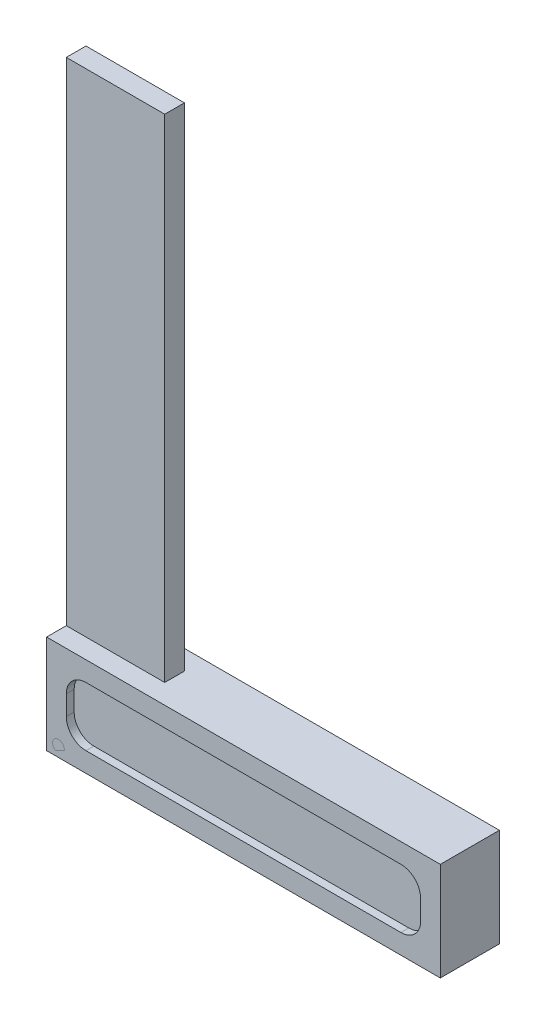
SolidWorks part; units mm, degrees
ref_plane "Plan de face" through (0, 0, 0) normal (0, 0, 1) x (1, 0, 0)
ref_plane "Plan de dessus" through (0, 0, 0) normal (0, 1, 0) x (1, 0, 0)
ref_plane "Plan de droite" through (0, 0, 0) normal (1, 0, 0) x (0, 0, -1)
sketch "Esquisse1" plane through (0, 0, 0) normal (0, 0, 1) x (1, 0, 0)
  line L1 (0, 0) -> (100, 0)
  line L2 (0, 0) -> (0, 25)
  line L3 (0, 25) -> (100, 25)
  line L4 (100, 0) -> (100, 25)
  dimension "D1" = 25
  dimension "D2" = 100
extrude "Boss.-Extru.1" add sketch "Esquisse1" along normal blind 15
sketch "Esquisse2" plane through (0, 0, 0) normal (-1, 0, 0) x (0, 0, 1)
  line L0 (15, 0) -> (0, 0) construction
  line L1 (5, 0) -> (10, 0)
  line L2 (5, 0) -> (5, 25)
  line L4 (10, 0) -> (10, 25)
  line L5 (15, 25) -> (0, 25) construction
  line L6 (7.5, 0) -> (7.5, 25) construction
  line L7 (5, 25) -> (5, 150)
  line L8 (5, 150) -> (10, 150)
  line L9 (10, 150) -> (10, 25)
  point P11 (4.5, 25)
  dimension "D1" = 5
  dimension "D2" = 150
extrude "Boss.-Extru.2" add sketch "Esquisse2" against normal blind 25 separate body
sketch "Esquisse3" plane through (0, 0, 15) normal (0, 0, 1) x (1, 0, 0)
  line L0 (95, 12.5) -> (100, 12.5) construction
  line L1 (5, 20) -> (95, 20)
  line L2 (5, 20) -> (5, 5)
  line L3 (5, 5) -> (95, 5)
  line L4 (95, 20) -> (95, 5)
  line L5 (100, 0) -> (100, 25) construction
  line L6 (50, 0) -> (50, 5) construction
  line L7 (0, 0) -> (100, 0) construction
  dimension "D1" = 15
  dimension "D2" = 90
extrude "Enlèv. mat.-Extru.1" cut sketch "Esquisse3" against normal blind 2
fillet "Congé1" radius 5 4 edges at (95, 5, 14) (95, 20, 14) (5, 5, 14) (5, 20, 14)
sketch "Esquisse4" plane through (0, 0, 15) normal (0, 0, 1) x (1, 0, 0)
  line L0 (0, 25) -> (0, 0) construction
  line L1 (0, 0) -> (100, 0) construction
  line L2 (100, 25) -> (0, 25) construction
  line L3 (25, 0) -> (25, 150) construction
  circle A0 centre (22.5, 22.5) radius 1.5
  circle A1 centre (3, 2.5) radius 1.5
  dimension "D1" = 3
  dimension "D2" = 3
  dimension "D4" = 2.5
  dimension "D5" = 2.5
  dimension "D3" = 2.5
extrude "Boss.-Extru.3" add sketch "Esquisse4" against normal up to vertex (15 mm away) separate body
